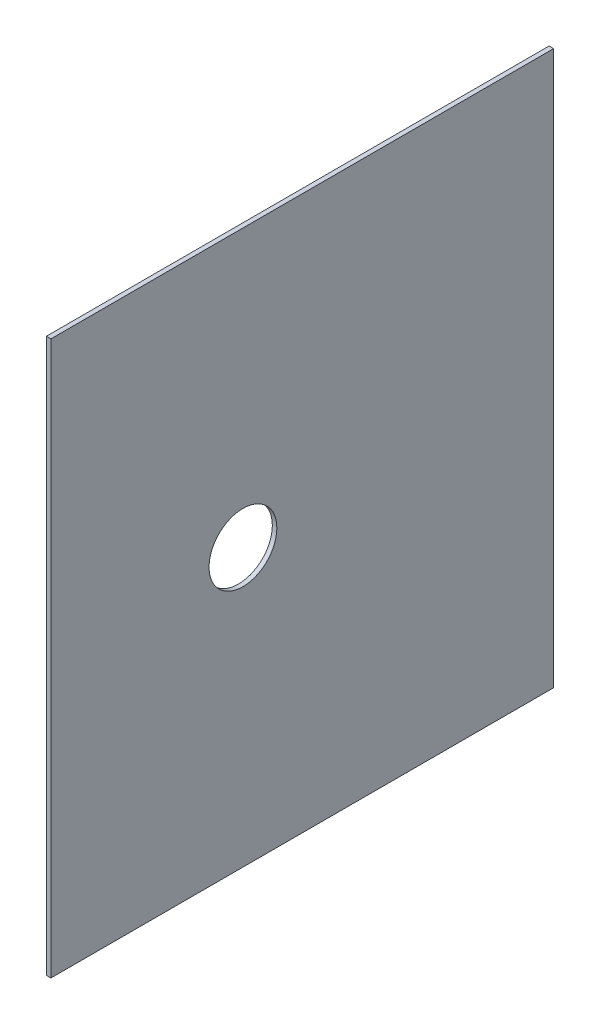
SolidWorks part; units mm, degrees
ref_plane "Front Plane" through (0, 0, 0) normal (0, 0, 1) x (1, 0, 0)
ref_plane "Top Plane" through (0, 0, 0) normal (0, 1, 0) x (1, 0, 0)
ref_plane "Right Plane" through (0, 0, 0) normal (1, 0, 0) x (0, 0, -1)
sketch "Sketch1" plane through (0, 0, 0) normal (1, 0, 0) x (0, 0, -1)
  line L1 (0, 0) -> (445, 0)
  line L2 (0, 0) -> (0, 490)
  line L3 (0, 490) -> (445, 490)
  line L4 (445, 0) -> (445, 490)
  circle A0 centre (170, 245) radius 30
  dimension "D3" = 60
  dimension "D4" = 170
  dimension "D1" = 445
  dimension "D2" = 490
  dimension "D5" = 245
extrude "Boss-Extrude1" add sketch "Sketch1" along normal blind 4
